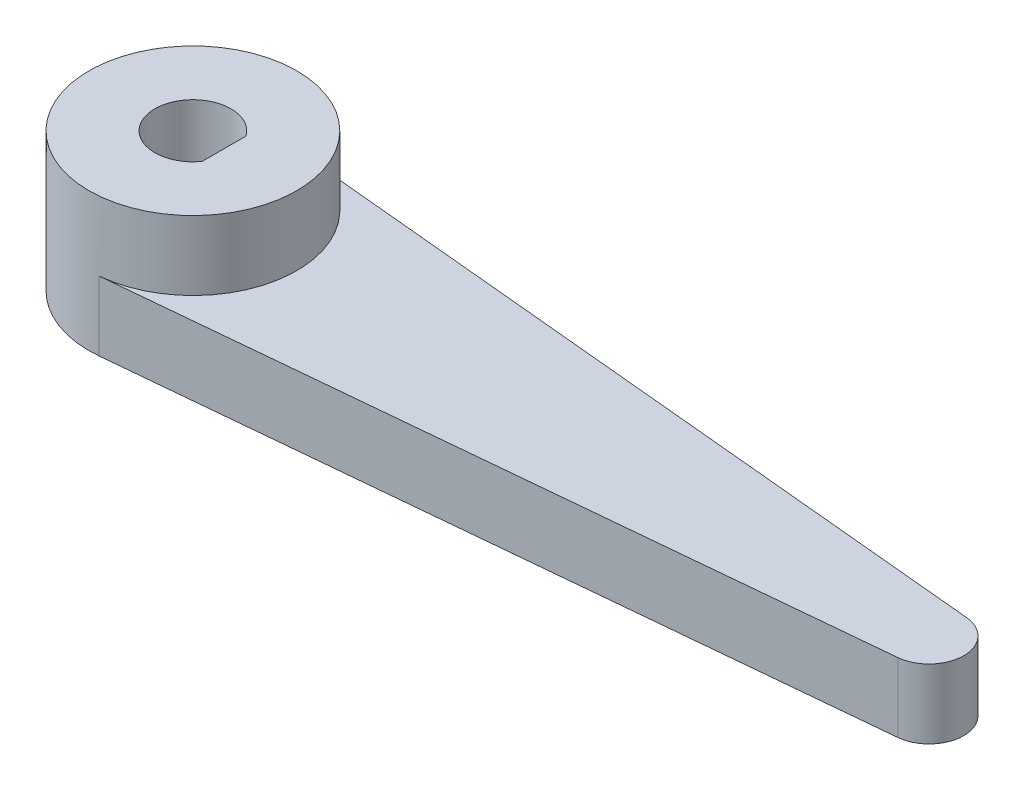
SolidWorks part; units mm, degrees
ref_plane "前视基准面" through (0, 0, 0) normal (0, 0, 1) x (1, 0, 0)
ref_plane "上视基准面" through (0, 0, 0) normal (0, 1, 0) x (1, 0, 0)
ref_plane "右视基准面" through (0, 0, 0) normal (1, 0, 0) x (0, 0, -1)
sketch "草图1" plane through (0, 0, 0) normal (0, 1, 0) x (1, 0, 0)
  line L0 (0, 0) -> (53.1451, 0) construction
  line L1 (0.7056, 7.4667) -> (53.3803, 2.4889)
  line L2 (0.7056, -7.4667) -> (53.3803, -2.4889)
  arc A0 (0.7056, 7.4667) -> (0.7056, -7.4667) centre (0, 0) ccw
  arc A1 (53.3803, -2.4889) -> (53.3803, 2.4889) centre (53.1451, 0) ccw
  dimension "D1" = 15
  dimension "D2" = 5
extrude "凸台-拉伸1" add sketch "草图1" along normal blind 5
sketch "草图2" plane through (0, 5, 0) normal (0, 1, 0) x (1, 0, 0)
  circle A0 centre (0, 0) radius 7.5
  arc A1 (0.7056, 7.4667) -> (0.7056, -7.4667) centre (0, 0) ccw construction
extrude "凸台-拉伸2" add sketch "草图2" along normal blind 5
sketch "草图3" plane through (0, 10, 0) normal (0, 1, 0) x (1, 0, 0)
  line L0 (2.25, 1.5811) -> (2.25, -1.5811)
  arc A0 (2.25, 1.5811) -> (2.25, -1.5811) centre (0, 0) ccw
  point P1 (-2.75, 0)
  dimension "D1" = 5.5
  dimension "D2" = 5
extrude "切除-拉伸1" cut sketch "草图3" against normal through all
